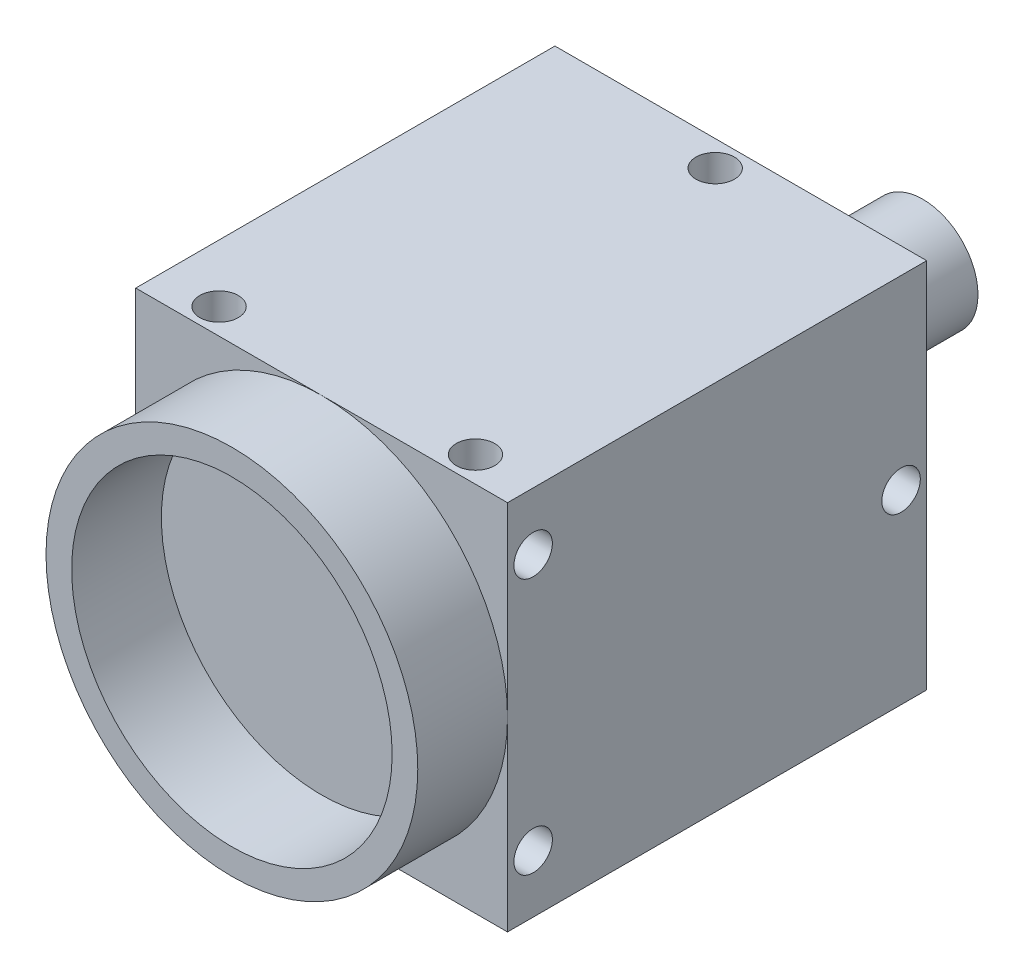
SolidWorks part; units mm, degrees
ref_plane "前视基准面" through (0, 0, 0) normal (0, 0, 1) x (1, 0, 0)
ref_plane "上视基准面" through (0, 0, 0) normal (0, 1, 0) x (1, 0, 0)
ref_plane "右视基准面" through (0, 0, 0) normal (1, 0, 0) x (0, 0, -1)
sketch "草图1" plane through (0, 0, 0) normal (0, 1, 0) x (1, 0, 0)
  line L1 (-14.5, 16.35) -> (14.5, 16.35)
  line L2 (-14.5, 16.35) -> (-14.5, -16.35)
  line L3 (-14.5, -16.35) -> (14.5, -16.35)
  line L4 (14.5, 16.35) -> (14.5, -16.35)
  line L5 (-14.5, 16.35) -> (14.5, -16.35) construction
  line L6 (-14.5, -16.35) -> (14.5, 16.35) construction
  point P0 (0, 0)
  dimension "D1" = 32.7
  dimension "D2" = 29
extrude "凸台-拉伸1" add sketch "草图1" along normal blind 29
sketch "草图2" plane through (0, 0, 16.35) normal (0, 0, 1) x (1, 0, 0)
  line L0 (-14.5, 14.5) -> (14.5, 14.5) construction
  line L1 (-14.5, 29) -> (-14.5, 0) construction
  line L2 (14.5, 29) -> (14.5, 0) construction
  circle A0 centre (0, 14.5) radius 14.5
  circle A1 centre (0, 14.5) radius 12.5
  dimension "D1" = 2
extrude "凸台-拉伸2" add sketch "草图2" along normal blind 7
sketch "草图3" plane through (0, 0, 0) normal (0, -1, 0) x (1, 0, 0)
  line L1 (-10, 14.35) -> (10, 14.35) construction
  line L2 (-10, 14.35) -> (-10, -14.35) construction
  line L3 (-10, -14.35) -> (10, -14.35) construction
  line L4 (10, 14.35) -> (10, -14.35) construction
  line L5 (-10, 14.35) -> (10, -14.35) construction
  line L6 (-10, -14.35) -> (10, 14.35) construction
  circle A0 centre (-10, 14.35) radius 1.5
  circle A1 centre (10, 14.35) radius 1.5
  circle A2 centre (-10, -14.35) radius 1.5
  circle A3 centre (10, -14.35) radius 1.5
  point P0 (0, 0)
  dimension "D3" = 3
  dimension "D1" = 20
  dimension "D2" = 28.7
extrude "切除-拉伸1" cut sketch "草图3" against normal blind 5
sketch "草图4" plane through (0, 29, 0) normal (0, 1, 0) x (1, 0, 0)
  line L0 (0, 16.35) -> (0, -16.35) construction
  line L1 (14.5, 16.35) -> (-14.5, 16.35) construction
  line L2 (0, 14.35) -> (10, -14.35) construction
  circle A0 centre (0, 14.35) radius 1.5
  circle A1 centre (-10, -14.35) radius 1.5
  circle A2 centre (10, -14.35) radius 1.5
  point P11 (5, 0)
  dimension "D1" = 3
  dimension "D2" = 28.7
  dimension "D3" = 20
extrude "切除-拉伸2" cut sketch "草图4" against normal blind 2.9
sketch "草图5" plane through (0, 0, -16.35) normal (0, 0, -1) x (-1, 0, 0)
  line L0 (-14.5, 29) -> (-14.5, 0) construction
  line L1 (-14.5, 29) -> (14.5, 29) construction
  circle A0 centre (-7.3, 21.8) radius 4.3
  circle A1 centre (-7.3, 21.8) radius 3.5
  dimension "D1" = 8.6
  dimension "D2" = 7.2
  dimension "D3" = 7.2
  dimension "D4" = 0.8
extrude "凸台-拉伸3" add sketch "草图5" along normal blind 6.9
sketch "草图6" plane through (0, 0, -16.35) normal (0, 0, -1) x (-1, 0, 0)
  line L1 (-8.15, 15.8) -> (8.15, 15.8)
  line L2 (-8.15, 15.8) -> (-8.15, 0)
  line L3 (-8.15, 0) -> (8.15, 0)
  line L4 (8.15, 15.8) -> (8.15, 0)
  line L5 (-8.15, 15.8) -> (8.15, 0) construction
  line L6 (-8.15, 0) -> (8.15, 15.8) construction
  point P0 (0, 7.9)
  point P5 (0, 0)
  dimension "D1" = 16.3
  dimension "D2" = 15.8
extrude "凸台-拉伸4" add sketch "草图6" along normal blind 2
pattern_circular "阵列(圆周)1" count 4 every 90 about axis through (0, 14.5, 0) along (0, 0, 1) skipping 2 of "切除-拉伸2"
